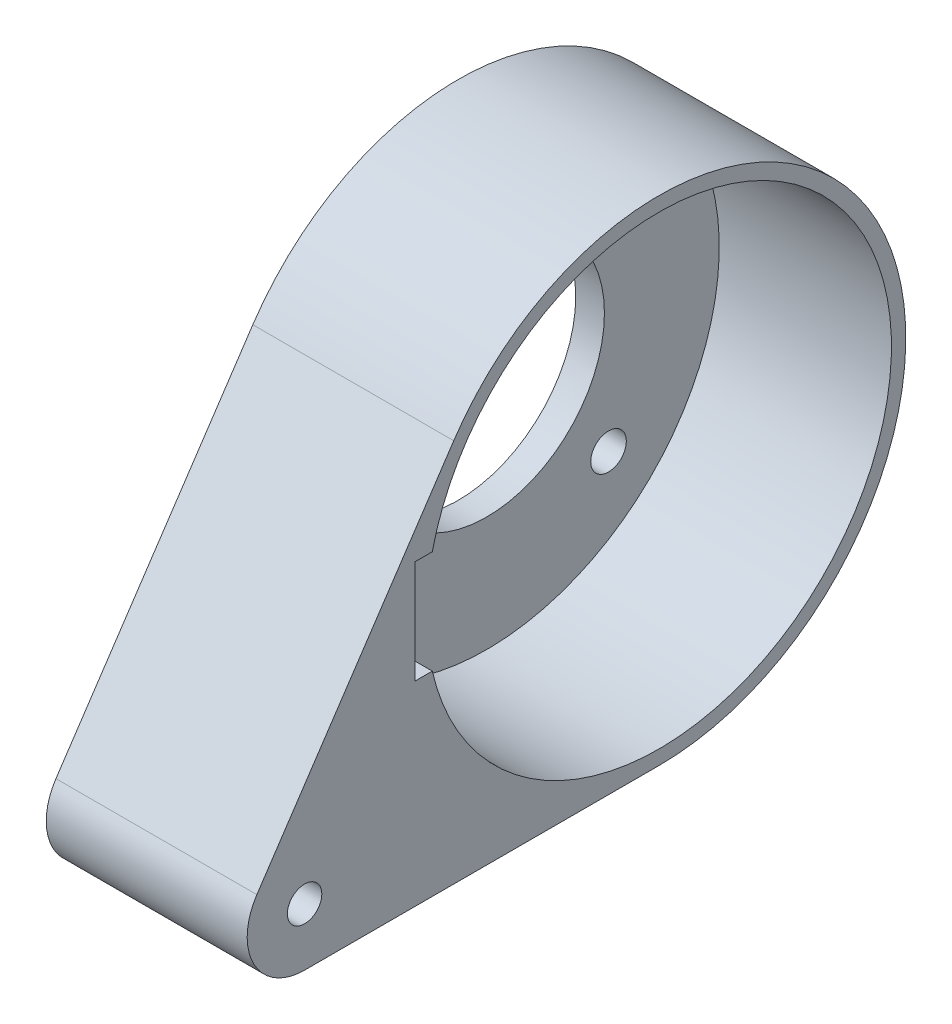
SolidWorks part; units mm, degrees
material "ABS"
ref_plane "Спереди" through (0, 0, 0) normal (0, 0, 1) x (1, 0, 0)
ref_plane "Сверху" through (0, 0, 0) normal (0, 1, 0) x (1, 0, 0)
ref_plane "Справа" through (0, 0, 0) normal (1, 0, 0) x (0, 0, -1)
sketch "Эскиз1" plane through (0, 0, 0) normal (1, 0, 0) x (0, 0, -1)
  line L0 (-30.8666, -21.5) -> (0, -21.5)
  line L1 (-30.8666, -16.5) -> (0, 0) construction
  line L2 (-35.0242, -13.7224) -> (-17.8775, 11.9435)
  arc A0 (0, -21.5) -> (-17.8775, 11.9435) centre (0, 0) ccw
  arc A1 (-35.0242, -13.7224) -> (-30.8666, -21.5) centre (-30.8666, -16.5) ccw
  dimension "D1" = 43
  dimension "D2" = 10
  dimension "D3" = 35
extrude "Бобышка-Вытянуть1" add sketch "Эскиз1" along normal blind 2.5
sketch "Эскиз2" plane through (2.5, 0, 0) normal (-1, 0, 0) x (0, 0, 1)
  line L0 (0, -21.5) -> (30.8666, -21.5)
  line L1 (17.8775, 11.9435) -> (35.0242, -13.7224)
  arc A0 (17.8775, 11.9435) -> (0, -21.5) centre (0, 0) ccw
  circle A1 centre (0, 0) radius 20.25
  circle A2 centre (0, 0) radius 21.5 construction
  arc A3 (30.8666, -21.5) -> (35.0242, -13.7224) centre (30.8666, -16.5) ccw
  arc A4 (30.8666, -21.5) -> (35.0242, -13.7224) centre (30.8666, -16.5) ccw construction
  dimension "D1" = 40.5
sketch "Эскиз3" plane through (2.5, 0, 0) normal (1, 0, 0) x (0, 0, -1)
  line L0 (0, 0) -> (0, 15) construction
  line L1 (0, 0) -> (0, -15) construction
  line L2 (0, 0) -> (-10.6066, -10.6066) construction
  line L4 (0, 0) -> (-15, 0) construction
  circle A0 centre (0, 0) radius 15 construction
  circle A1 centre (-10.6066, -10.6066) radius 1.55 construction
  circle A2 centre (-3.8823, 14.4889) radius 1.55 construction
  circle A3 centre (14.4889, -3.8823) radius 1.55 construction
  circle A4 centre (0, 0) radius 10.25
  circle A5 centre (3.8823, 14.4889) radius 1.55
  circle A6 centre (10.6066, -10.6066) radius 1.55
  circle A7 centre (-14.4889, -3.8823) radius 1.55
  point P13 (0, 0)
  dimension "D1" = 30
  dimension "D2" = 3.1
  dimension "D5" = 20.5
  dimension "D4" = 45
  dimension "D3" = 3
extrude "Вырез-Вытянуть1" cut sketch "Эскиз3" against normal up to surface (2.5 mm away) up to face at (0, -7.7777, 14.5498)
extrude "Бобышка-Вытянуть2" add sketch "Эскиз2" against normal blind 15
sketch "Эскиз4" plane through (17.5, 0, 0) normal (1, 0, 0) x (0, 0, -1)
  circle A0 centre (-30.8666, -16.5) radius 1.5
  arc A1 (-35.0242, -13.7224) -> (-30.8666, -21.5) centre (-30.8666, -16.5) ccw construction
  dimension "D1" = 3
extrude "Вырез-Вытянуть2" cut sketch "Эскиз4" against normal through all
sketch "Эскиз5" plane through (17.5, 0, 0) normal (1, 0, 0) x (0, 0, -1)
  line L0 (-20.25, 4.5) -> (-19.7437, 4.5)
  line L1 (-20.25, 4.5) -> (-21.25, 4.5)
  line L2 (-20.25, 4.5) -> (-20.25, -4.5) construction
  line L3 (-20.25, -4.5) -> (-21.25, -4.5)
  line L4 (-21.25, 4.5) -> (-21.25, -4.5)
  line L5 (-20.25, -4.5) -> (-19.7437, -4.5)
  line L6 (-19.7437, 4.5) -> (-19.7437, -4.5)
  circle A0 centre (0, 0) radius 20.25 construction
  circle A1 centre (0, 0) radius 20.25 construction
  point P6 (-20.25, 0)
  dimension "D1" = 1
  dimension "D2" = 9
extrude "Вырез-Вытянуть3" cut sketch "Эскиз5" against normal offset from surface (11 mm away) 4 up to face at (2.5, 0, -10.25)
